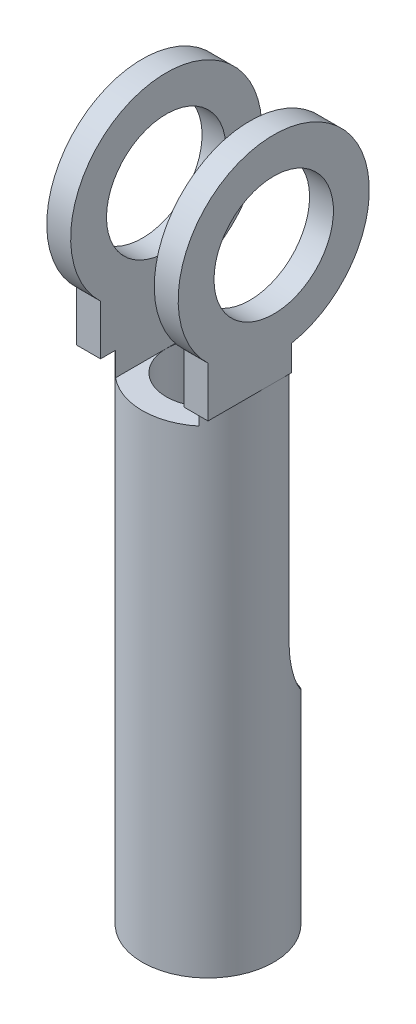
SolidWorks part; units mm, degrees
ref_plane "前基準面" through (0, 0, 0) normal (0, 0, 1) x (1, 0, 0)
ref_plane "上基準面" through (0, 0, 0) normal (0, 1, 0) x (1, 0, 0)
ref_plane "右基準面" through (0, 0, 0) normal (1, 0, 0) x (0, 0, -1)
sketch "草圖1" plane through (0, 0, 0) normal (0, 1, 0) x (1, 0, 0)
  circle A0 centre (0, 0) radius 2.75
  circle A1 centre (0, 0) radius 1.75
  dimension "D1" = 5.5
  dimension "D2" = 1
extrude "伸長1" add sketch "草圖1" along normal blind 20
sketch "草圖2" plane through (0, 0, 0) normal (1, 0, 0) x (0, 0, -1)
  line L0 (0.75, 20) -> (0.75, 11.1623)
  line L1 (1.75, 20) -> (-1.75, 20) construction
  line L2 (2.75, 0) -> (2.75, 20) construction
  line L4 (0.75, 20) -> (2.75, 20)
  line L5 (2.75, 20) -> (2.75, 8)
  arc A0 (0.75, 11.1623) -> (2.75, 8) centre (4.25, 11.1623) ccw
  dimension "D3" = 3.5
  dimension "D1" = 8
  dimension "D2" = 2
extrude "伸長2" cut sketch "草圖2" against normal through all and the other way through all
sketch "草圖3" plane through (0, 20, 0) normal (0, 1, 0) x (1, 0, 0)
  line L0 (0, 0) -> (-2.75, 0) construction
  line L1 (0, 0) -> (2.75, 0) construction
  line L2 (-2.75, 0) -> (-1.75, 0) construction
  line L3 (-2.75, 4) -> (-1.75, 4)
  line L4 (-2.75, 4) -> (-2.75, -4)
  line L5 (-2.75, -4) -> (-1.75, -4)
  line L6 (-1.75, 4) -> (-1.75, -4)
  line L7 (-2.75, 4) -> (-1.75, -4) construction
  line L8 (-2.75, -4) -> (-1.75, 4) construction
  line L9 (1.75, 4) -> (2.75, 4)
  line L10 (1.75, 4) -> (1.75, -4)
  line L11 (1.75, -4) -> (2.75, -4)
  line L12 (2.75, 4) -> (2.75, -4)
  line L13 (1.75, 4) -> (2.75, -4) construction
  line L14 (1.75, -4) -> (2.75, 4) construction
  line L15 (1.75, 0) -> (2.75, 0) construction
  line L16 (-1.75, 4) -> (1.75, 4) construction
  line L17 (1.75, -4) -> (-1.75, -4) construction
  arc A0 (-2.6458, 0.75) -> (2.6458, 0.75) centre (0, 0) ccw construction
  arc A1 (-1.5811, 0.75) -> (1.5811, 0.75) centre (0, 0) ccw construction
  point P7 (-2.25, 0)
  point P13 (2.25, 0)
  dimension "D1" = 8
extrude "伸長3" add sketch "草圖3" along normal blind 10
sketch "草圖4" plane through (-2.75, 0, 0) normal (-1, 0, 0) x (0, 0, 1)
  line L0 (-4, 30) -> (4, 30) construction
  line L1 (4, 30) -> (4, 20) construction
  line L2 (-0.75, 20) -> (-0.75, 22.0709)
  line L3 (2.75, 20) -> (2.75, 23.0953)
  line L5 (-0.75, 20) -> (-4, 20)
  line L6 (-4, 20) -> (-4, 30)
  line L7 (-4, 30) -> (-4, 20) construction
  line L8 (-4, 30) -> (4, 30)
  line L9 (4, 30) -> (4, 20)
  line L10 (4, 20) -> (2.75, 20)
  arc A0 (2.75, 23.0953) -> (-0.75, 22.0709) centre (0, 26) ccw
  circle A1 centre (0, 26) radius 2.5
  line M1 (-4, 20) -> (0, 20)
  line M2 (0, 20) -> (4, 20)
  line M3 (4, 20) -> (4, 30)
  line M4 (4, 30) -> (-4, 30)
  line M5 (-4, 30) -> (-4, 20)
  dimension "D1" = 8
  dimension "D2" = 5
extrude "伸長5" cut sketch "草圖4" against normal through all contours A0 L8 M3 | A0 M4 M5 | A0 L6 L2 M1 | A0 L3 L9 M2
sketch "草圖10" plane through (0, 20, 0) normal (0, -1, 0) x (1, 0, 0)
  line L0 (-2.75, 2.75) -> (2.75, 2.75)
  line L1 (2.75, 2.75) -> (2.75, -0.75)
  line L2 (2.75, -0.75) -> (2.6458, -0.75)
  line L3 (-2.75, -0.75) -> (-2.6458, -0.75)
  line L5 (-2.75, 2.75) -> (-2.75, -0.75)
  arc A0 (-2.75, 0) -> (-2.6458, -0.75) centre (0, 0) ccw construction
  arc A2 (0, 2.75) -> (-1.75, 2.1213) centre (0, 0) ccw construction
  arc A3 (1.75, 2.1213) -> (0, 2.75) centre (0, 0) ccw construction
  arc A4 (2.6458, -0.75) -> (2.75, 0) centre (0, 0) ccw construction
  arc A5 (2.75, 0) -> (1.75, 2.1213) centre (0, 0) ccw construction
  arc A6 (-2.75, 0) -> (-2.6458, -0.75) centre (0, 0) ccw
  arc A8 (0, 2.75) -> (-2.75, 0) centre (0, 0) ccw
  arc A9 (1.75, 2.1213) -> (0, 2.75) centre (0, 0) ccw
  arc A10 (2.6458, -0.75) -> (2.75, 0) centre (0, 0) ccw
  arc A11 (2.75, 0) -> (1.75, 2.1213) centre (0, 0) ccw
  line M1 (2.75, 2.75) -> (1.75, 2.75)
  line M2 (1.75, 2.75) -> (1.75, 2.1213)
  arc M3 (1.75, 2.1213) -> (2.75, 0) centre (0, 0) cw
  line M4 (2.75, 0) -> (2.75, 2.75)
extrude "伸長8" cut sketch "草圖10" against normal blind 1 contours A8 L0 L5 | M4 M1 M2 M3 | A9 L0 M2 | A6 L5 L3 | A10 L2 L1
